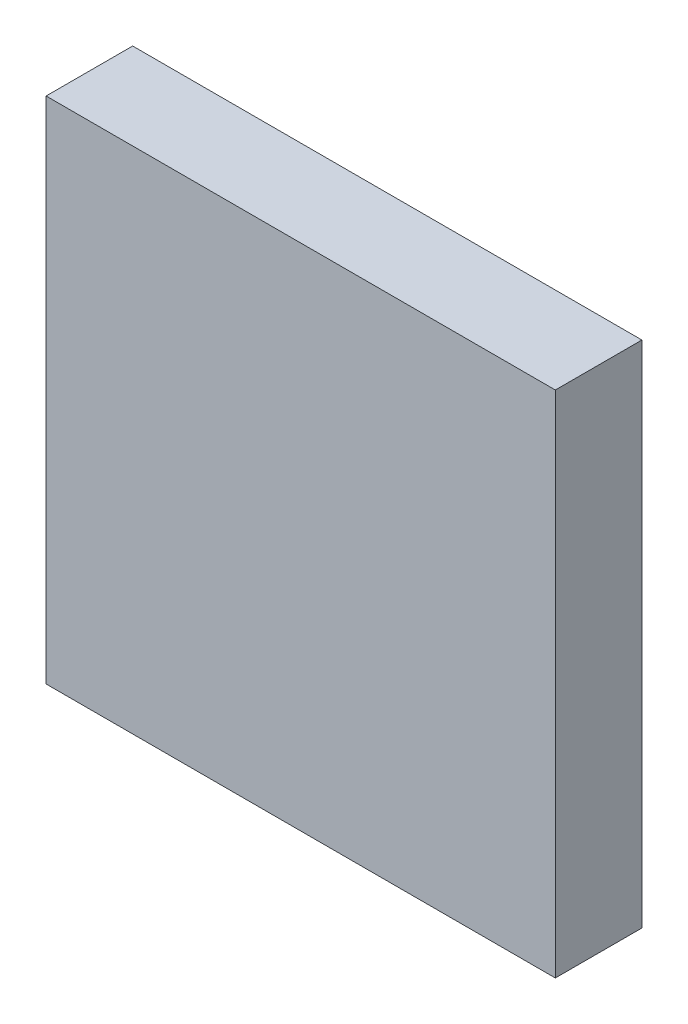
SolidWorks part; units mm, degrees
ref_plane "Front Plane" through (0, 0, 0) normal (0, 0, 1) x (1, 0, 0)
ref_plane "Top Plane" through (0, 0, 0) normal (0, 1, 0) x (1, 0, 0)
ref_plane "Right Plane" through (0, 0, 0) normal (1, 0, 0) x (0, 0, -1)
sketch "Sketch1" plane through (0, 0, 0) normal (0, 0, 1) x (1, 0, 0)
  line L1 (0, 0) -> (90, 0)
  line L2 (0, 0) -> (0, 90)
  line L3 (0, 90) -> (90, 90)
  line L4 (90, 0) -> (90, 90)
  dimension "D1" = 90
  dimension "D2" = 90
extrude "Boss-Extrude1" add sketch "Sketch1" along normal blind 15.3
